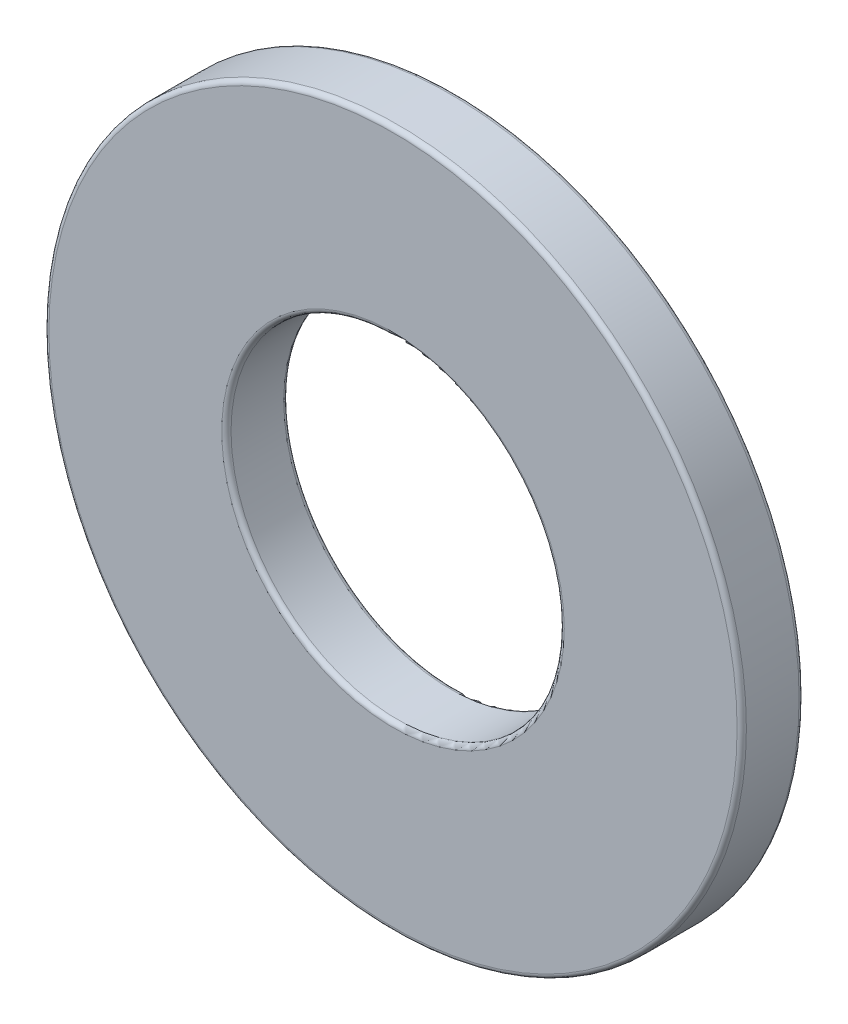
SolidWorks part; units mm, degrees
ref_plane "Front Plane" through (0, 0, 0) normal (0, 0, 1) x (1, 0, 0)
ref_plane "Top Plane" through (0, 0, 0) normal (0, 1, 0) x (1, 0, 0)
ref_plane "Right Plane" through (0, 0, 0) normal (1, 0, 0) x (0, 0, -1)
sketch "Sketch1" plane through (0, 0, 0) normal (0, 0, 1) x (1, 0, 0)
  line L0 (0, 0) -> (2.15, 0) construction
  line L1 (0, -0.165) -> (0, 0.165) construction
  circle A0 centre (0, 0) radius 4.5
  circle A1 centre (0, 0) radius 2.15
  dimension "D1" = 90
  dimension "OD" = 9
  dimension "ID" = 4.3
sketch "Sketch2" plane through (0, 0, 0) normal (1, 0, 0) x (0, 0, -1)
  line L0 (-0.4, 4.5) -> (0.4, 4.5) construction
  point P5 (0, 4.5)
  dimension "Thickness" = 0.8
sketch "Sketch3" plane through (0, 0, 0) normal (0, 0, 1) x (1, 0, 0)
  circle A0 centre (0, 0) radius 2.15 construction
  circle A1 centre (0, 0) radius 4.5 construction
  circle A2 centre (0, 0) radius 2.15
  circle A3 centre (0, 0) radius 4.5
extrude "Boss-Extrude1" add sketch "Sketch3" against normal up to vertex (0.4 mm away) from vertex at 0.4 starting at point (0, 4.5, 0.4)
fillet "Fillet1" radius 0.06 4 edges at (4.5, 0, 0.4) (2.15, 0, 0.4) (4.5, 0, -0.4) (2.15, 0, -0.4)
